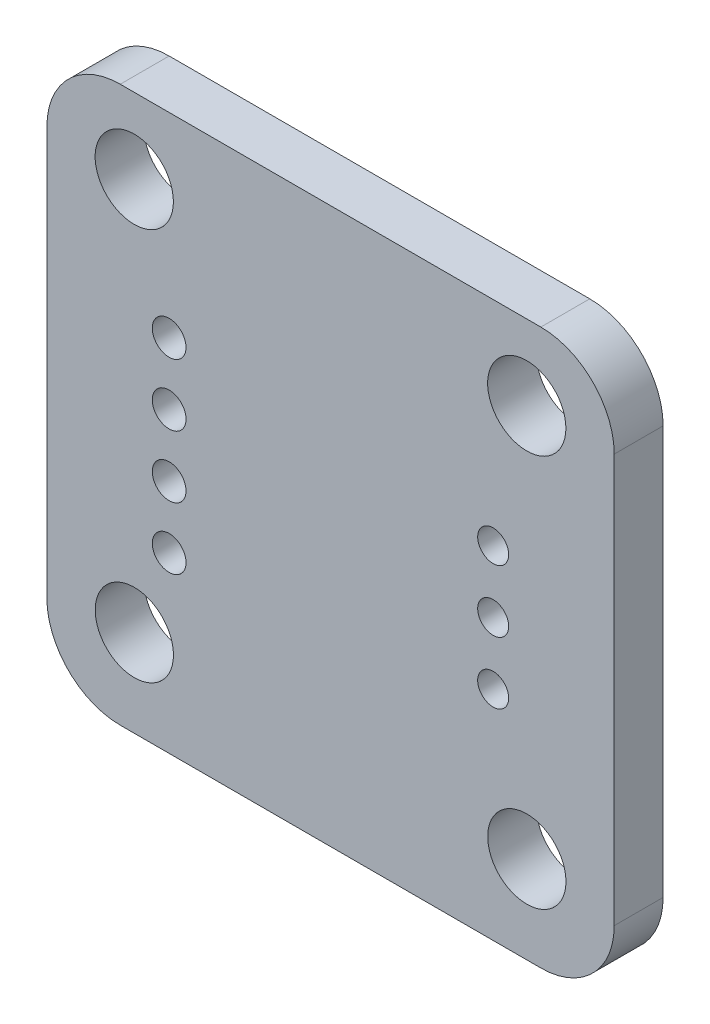
SolidWorks part; units mm, degrees
ref_plane "Front Plane" through (0, 0, 0) normal (0, 0, 1) x (1, 0, 0)
ref_plane "Top Plane" through (0, 0, 0) normal (0, 1, 0) x (1, 0, 0)
ref_plane "Right Plane" through (0, 0, 0) normal (1, 0, 0) x (0, 0, -1)
sketch "Sketch1" plane through (0, 0, 0) normal (0, 0, 1) x (1, 0, 0)
  line L2 (-11.6029, 11.1029) -> (11.5971, 11.1029)
  line L3 (-11.6029, 11.1029) -> (-11.6029, -11.5971)
  line L4 (-11.6029, -11.5971) -> (11.5971, -11.5971)
  line L5 (11.5971, 11.1029) -> (11.5971, -11.5971)
  line L6 (-0.0029, -11.5971) -> (-0.0029, 11.1029) construction
  line L7 (-11.6029, -0.2471) -> (11.5971, -0.2471) construction
  circle A0 centre (-8.0298, 8.0242) radius 1.6
  circle A1 centre (8.0213, 8.0269) radius 1.6
  circle A2 centre (8.024, -8.0242) radius 1.6
  circle A3 centre (-8.0271, -8.0269) radius 1.6
  point P2 (-0.0029, 0)
  point P7 (-0.0029, -0.2471)
  dimension "D3" = 3.2
  dimension "D1" = 23.2
  dimension "D2" = 22.7
extrude "Boss-Extrude1" add sketch "Sketch1" along normal blind 2
fillet "Fillet1" radius 3 4 edges at (11.5971, -11.5971, 1) (-11.6029, -11.5971, 1) (-11.6029, 11.1029, 1) (11.5971, 11.1029, 1)
sketch "Sketch2" plane through (0, 0, 2) normal (0, 0, 1) x (1, 0, 0)
  line L0 (-11.6029, 8.1029) -> (-11.6029, -8.5971) construction
  line L1 (-8.6029, -11.5971) -> (8.5971, -11.5971) construction
  line L2 (11.5971, -8.5971) -> (11.5971, 8.1029) construction
  circle A0 centre (6.6471, -2.6971) radius 0.6336
  circle A1 centre (6.6471, -0.1571) radius 0.6336
  circle A2 centre (6.6471, 2.3829) radius 0.6336
  circle A3 centre (-6.6029, -4.4971) radius 0.6903
  circle A4 centre (-6.6029, -1.9571) radius 0.6903
  circle A5 centre (-6.6029, 0.5829) radius 0.6903
  circle A6 centre (-6.6029, 3.1229) radius 0.6903
  point P18 (-12.5749, -6.6819)
  dimension "D1" = 3
  dimension "D2" = 4
  dimension "D3" = 5
  dimension "D4" = 7.1
  dimension "D5" = 8.9
  dimension "D6" = 4.95
extrude "Cut-Extrude1" cut sketch "Sketch2" against normal through all
